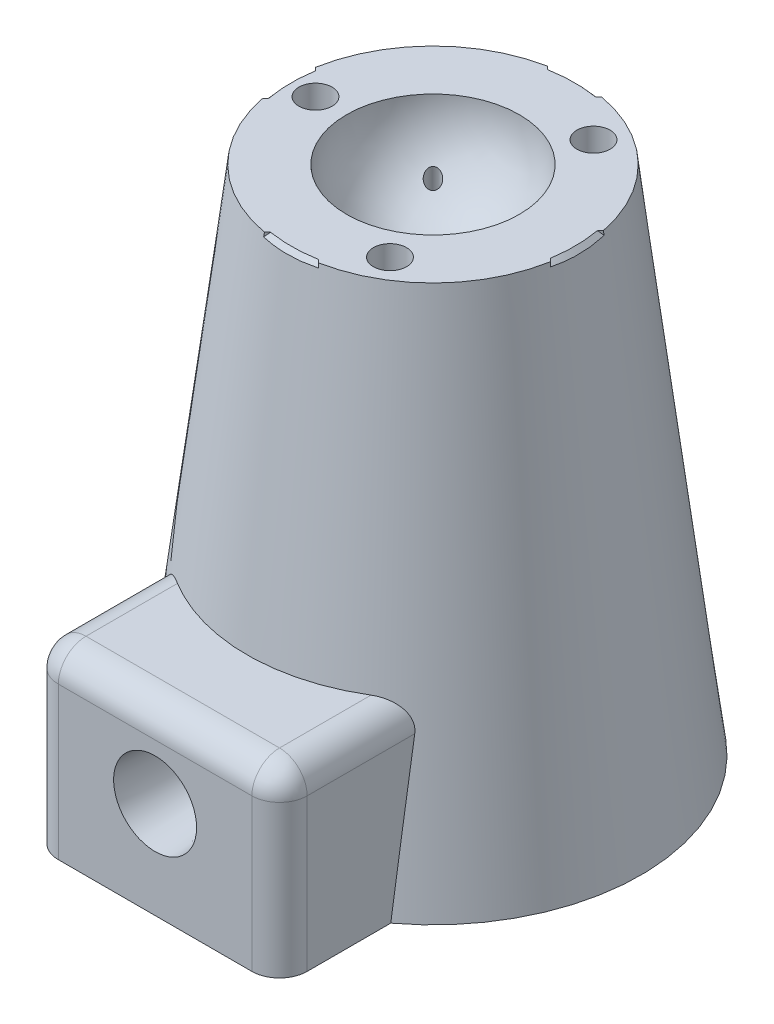
SolidWorks part; units mm, degrees
ref_plane "前视基准面" through (0, 0, 0) normal (0, 0, 1) x (1, 0, 0)
ref_plane "上视基准面" through (0, 0, 0) normal (0, 1, 0) x (1, 0, 0)
ref_plane "右视基准面" through (0, 0, 0) normal (1, 0, 0) x (0, 0, -1)
other "Configuration Table"
sketch "草图2" plane through (0, 0, 0) normal (0, 1, 0) x (1, 0, 0)
  line L1 (-28.1, 43.1) -> (28.1, 43.1)
  line L2 (-43.1, 28.1) -> (-43.1, -28.1)
  line L3 (-28.1, -43.1) -> (28.1, -43.1)
  line L4 (43.1, 28.1) -> (43.1, -28.1)
  line L5 (-43.1, 43.1) -> (43.1, -43.1) construction
  line L6 (-43.1, -43.1) -> (43.1, 43.1) construction
  arc A0 (-43.1, -28.1) -> (-28.1, -43.1) centre (-28.1, -28.1) ccw
  arc A1 (28.1, -43.1) -> (43.1, -28.1) centre (28.1, -28.1) ccw
  arc A2 (28.1, 43.1) -> (43.1, 28.1) centre (28.1, 28.1) cw
  arc A3 (-28.1, 43.1) -> (-43.1, 28.1) centre (-28.1, 28.1) ccw
  point P0 (0, 0)
  dimension "D3" = 15
  dimension "D1" = 86.2
  dimension "D2" = 86.2
extrude "凸台-拉伸1" add sketch "草图2" along normal blind 10
sketch "草图3" plane through (0, 10, 0) normal (0, 1, 0) x (1, 0, 0)
  line L0 (0, 6.25) -> (0, -6.25)
  arc A0 (0, 6.25) -> (0, -6.25) centre (0, 0) ccw
revolve "切除-旋转1" cut sketch "草图3" angle 360 about L0
ref_plane "基准面4" through (0, 0, 10) normal (0, 0, 1) x (1, 0, 0)
sketch "草图4" plane through (0, 10, 0) normal (0, 1, 0) x (1, 0, 0)
  line L0 (0, 0) -> (-37.5181, 37.5181) construction
sketch "草图5" plane through (0, 0, 0) normal (0, 0, 1) x (1, 0, 0)
  line L0 (0, 0) -> (0, 23.5244) construction
ref_plane "基准面2" through (0, 0, 0) normal (0.7071, 0, -0.7071) x (0, 1, 0)
sketch "草图22" plane through (0, 0, 0) normal (0, -1, 0) x (1, 0, 0)
  line L8 (-43.1, 28.1) -> (-43.1, -28.1)
  line L9 (-28.1, -43.1) -> (28.1, -43.1)
  line L10 (43.1, -28.1) -> (43.1, 28.1)
  line L11 (28.1, 43.1) -> (-28.1, 43.1)
  line L12 (-43.1, 28.1) -> (-43.1, -28.1)
  line L13 (-28.1, -43.1) -> (28.1, -43.1)
  line L14 (43.1, -28.1) -> (43.1, 28.1)
  line L15 (28.1, 43.1) -> (-28.1, 43.1)
  arc A8 (-28.1, 43.1) -> (-43.1, 28.1) centre (-28.1, 28.1) ccw
  arc A9 (-43.1, -28.1) -> (-28.1, -43.1) centre (-28.1, -28.1) ccw
  arc A10 (28.1, -43.1) -> (43.1, -28.1) centre (28.1, -28.1) ccw
  arc A11 (43.1, 28.1) -> (28.1, 43.1) centre (28.1, 28.1) ccw
  arc A12 (-28.1, 43.1) -> (-43.1, 28.1) centre (-28.1, 28.1) ccw
  arc A13 (-43.1, -28.1) -> (-28.1, -43.1) centre (-28.1, -28.1) ccw
  arc A14 (28.1, -43.1) -> (43.1, -28.1) centre (28.1, -28.1) ccw
  arc A15 (43.1, 28.1) -> (28.1, 43.1) centre (28.1, 28.1) ccw
  dimension "D1" = 0
extrude "凸台-拉伸2" add sketch "草图22" along normal blind 20
sketch "草图7" plane through (0, 0, 0) normal (0.7071, 0, -0.7071) x (0, 1, 0)
  line L0 (0.163, 0) -> (28.4458, 0) construction
  line L1 (0, 0) -> (23.5244, 0) construction
  line L2 (28.4458, 0) -> (-23.7376, 10.6911)
sweep "切除-扫描1" cut path "草图7" circular profile diameter 1 parameters "D3"=1
pattern_circular "阵列(圆周)1" count 4 over 360 about axis through (0, 10, 0) along (0, 1, 0) of "切除-扫描1"
ref_plane "基准面3" through (0, -20, 0) normal (0, 1, 0) x (1, 0, 0)
sketch "草图277" plane through (0, -20, 0) normal (0, 1, 0) x (1, 0, 0)
  line L1 (-28.1, -43.1) -> (28.1, -43.1)
  line L2 (-43.1, -28.1) -> (-43.1, 28.1)
  line L3 (-28.1, 43.1) -> (28.1, 43.1)
  line L4 (43.1, -28.1) -> (43.1, 28.1)
  line L5 (-43.1, -43.1) -> (43.1, 43.1) construction
  line L6 (-43.1, 43.1) -> (43.1, -43.1) construction
  arc A0 (-43.1, 28.1) -> (-28.1, 43.1) centre (-28.1, 28.1) cw
  arc A1 (28.1, 43.1) -> (43.1, 28.1) centre (28.1, 28.1) cw
  arc A2 (28.1, -43.1) -> (43.1, -28.1) centre (28.1, -28.1) ccw
  arc A3 (-28.1, -43.1) -> (-43.1, -28.1) centre (-28.1, -28.1) cw
  point P0 (0, 0)
  dimension "D3" = 15
  dimension "D1" = 86.2
  dimension "D2" = 86.2
extrude "凸台-拉伸5" add sketch "草图277" against normal blind 7
sketch "草图248" plane through (0, -20, 0) normal (0, 1, 0) x (1, 0, 0)
  line L0 (0, 0) -> (-7.0183, 7.0183)
  line L1 (0, 0) -> (-37.5181, 37.5181) construction
sweep "切除-扫描16" cut path "草图248" circular profile diameter 2.5 parameters "D3"=2.5
sketch "草图197" plane through (0, -20, 0) normal (0, 1, 0) x (1, 0, 0)
  line L0 (0, -3.5) -> (0, 3.5)
  arc A0 (0, 3.5) -> (0, -3.5) centre (0, 0) ccw
  dimension "D1" = 7
revolve "切除-旋转2" cut sketch "草图197" angle 360 about L0
sketch "草图303" plane through (0, -20, 0) normal (0, 1, 0) x (1, 0, 0)
  line L0 (0, 0) -> (-37.5181, 37.5181) construction
  line L1 (-7.0179, 5.7679) -> (-7.0179, 8.2679)
  arc A0 (-7.0179, 8.2679) -> (-7.0179, 5.7679) centre (-7.0179, 7.0179) ccw
  dimension "D1" = 2.5
revolve "切除-旋转5" cut sketch "草图303" angle 360 about L1
pattern_circular "阵列(圆周)3" count 4 over 360 about axis through (0, 0, 0) along (0, 1, 0) of "切除-扫描16", "切除-旋转5"
sketch "草图310" plane through (0, 10, 0) normal (0, 1, 0) x (1, 0, 0)
  line L0 (0, 0) -> (-37.5181, 37.5181) construction
  line L1 (28.1, 43.1) -> (-28.1, 43.1) construction
  circle A0 centre (-33.1, 33.1) radius 2.6
  circle A1 centre (33.1, 33.1) radius 2.6
  circle A2 centre (33.1, -33.1) radius 2.6
  circle A3 centre (-33.1, -33.1) radius 2.6
  point P15 (0, 0)
  dimension "D1" = 5.2
  dimension "D2" = 10
  dimension "D3" = 4
extrude "切除-拉伸2" cut sketch "草图310" against normal blind 10
sketch "草图311" plane through (0, 10, 0) normal (0, 1, 0) x (1, 0, 0)
  line L0 (-35.1, 26.6147) -> (-35.1, -26.6147)
  line L2 (-35.1, -26.6147) -> (-10.0896, -1.8063)
  line L3 (-35.1, 26.6147) -> (-10.119, 1.6337)
  line L4 (0, 0) -> (-37.5181, 37.5181) construction
  line L5 (-43.1, 28.1) -> (-43.1, -28.1) construction
  circle A3 centre (0, 0) radius 10.25
  arc A4 (-10.119, 1.6337) -> (-10.0896, -1.8063) centre (0, 0) ccw
  dimension "D2" = 6
  dimension "D4" = 8
  dimension "D1" = 4
sketch "草图316" plane through (0, -20, 0) normal (0, 1, 0) x (1, 0, 0)
  line L1 (-35.1, 26.6147) -> (-37.4121, 26.6147)
  line L2 (-35.1, 26.6147) -> (-35.1, -26.6147)
  line L3 (-35.1, -26.6147) -> (-37.4121, -26.6147)
  line L4 (-37.4121, 26.6147) -> (-37.4121, -26.6147)
loft "切除-放样5" cut profiles "草图311", "草图316"
sketch "草图317" plane through (0, -20, 0) normal (0, 1, 0) x (1, 0, 0)
  line L1 (-35.1, 26.6147) -> (-39.2405, 26.6147)
  line L2 (-35.1, 26.6147) -> (-35.1, -26.6147)
  line L3 (-35.1, -26.6147) -> (-39.2405, -26.6147)
  line L4 (-39.2405, 26.6147) -> (-39.2405, -26.6147)
extrude "凸台-拉伸6" add sketch "草图317" along normal blind 30
pattern_circular "阵列(圆周)5" count 4 over 360 about axis through (0, 10, 0) along (0, 1, 0) of "凸台-拉伸6", "切除-放样5"
sketch "草图326" plane through (0, -20, 0) normal (0, 1, 0) x (1, 0, 0)
  line L1 (-26.6147, -35.1) -> (26.6526, -35.1)
  line L2 (-26.6147, -35.1) -> (-26.6147, -32.173)
  line L3 (-26.6147, -32.173) -> (26.6526, -32.173)
  line L4 (26.6526, -35.1) -> (26.6526, -32.173)
extrude "凸台-拉伸7" add sketch "草图326" along normal blind 30
sketch "草图334" plane through (-43.1, 0, 0) normal (-1, 0, 0) x (0, 0, 1)
  line L0 (0, -27) -> (0, 1.7791) construction
  line L1 (-28.1, -27) -> (28.1, -27) construction
  line L2 (0, 0) -> (0, 23.5244) construction
  line L3 (-28.1, -8.5) -> (12.7158, -8.5) construction
  line L4 (-28.1, 10) -> (-28.1, -27) construction
  line L5 (-28.1, 10) -> (28.1, 10) construction
  line L6 (-17.1, 4) -> (17.1, 4)
  line L7 (-22.1, -1) -> (-22.1, -12)
  line L8 (-17.1, -17) -> (17.1, -17)
  line L9 (22.1, -1) -> (22.1, -12)
  line L10 (-22.1, 4) -> (22.1, -17) construction
  line L11 (-22.1, -17) -> (22.1, 4) construction
  arc A0 (17.1, -17) -> (22.1, -12) centre (17.1, -12) ccw
  arc A1 (17.1, 4) -> (22.1, -1) centre (17.1, -1) cw
  arc A2 (-22.1, -12) -> (-17.1, -17) centre (-17.1, -12) ccw
  arc A3 (-17.1, 4) -> (-22.1, -1) centre (-17.1, -1) ccw
  point P10 (0, -6.5)
  dimension "D2" = 5
  dimension "D1" = 10
  dimension "D3" = 6
  dimension "D4" = 6
extrude "切除-拉伸3" cut sketch "草图334" against normal blind 8
sketch "草图335" plane through (0, 0, -43.1) normal (0, 0, -1) x (-1, 0, 0)
  line L0 (-28.1, -27) -> (28.1, -27) construction
  line L1 (-17.1, 4) -> (17.1, 4)
  line L2 (-22.1, -1) -> (-22.1, -12)
  line L3 (-17.1, -17) -> (17.1, -17)
  line L4 (22.1, -1) -> (22.1, -12)
  line L5 (-22.1, 4) -> (22.1, -17) construction
  line L6 (-22.1, -17) -> (22.1, 4) construction
  line L7 (-28.1, 10) -> (28.1, 10) construction
  line L8 (-28.1, 10) -> (-28.1, -27) construction
  line L9 (28.1, 10) -> (28.1, -27) construction
  arc A0 (-22.1, -12) -> (-17.1, -17) centre (-17.1, -12) ccw
  arc A1 (17.1, -17) -> (22.1, -12) centre (17.1, -12) ccw
  arc A2 (17.1, 4) -> (22.1, -1) centre (17.1, -1) cw
  arc A3 (-17.1, 4) -> (-22.1, -1) centre (-17.1, -1) ccw
  point P0 (0, -6.5)
  dimension "D5" = 5
  dimension "D1" = 10
  dimension "D2" = 6
  dimension "D3" = 6
  dimension "D4" = 6
extrude "切除-拉伸4" cut sketch "草图335" against normal blind 8
sketch "草图336" plane through (43.1, 0, 0) normal (1, 0, 0) x (0, 0, -1)
  line L0 (0, 10) -> (37.5181, 10) construction
  line L1 (-17.1, 4) -> (17.1, 4)
  line L2 (-22.1, -1) -> (-22.1, -12)
  line L3 (-17.1, -17) -> (17.1, -17)
  line L4 (22.1, -1) -> (22.1, -12)
  line L5 (-22.1, 4) -> (22.1, -17) construction
  line L6 (-22.1, -17) -> (22.1, 4) construction
  line L7 (28.1, 10) -> (28.1, -27) construction
  line L8 (-28.1, 10) -> (-28.1, -27) construction
  line L9 (-28.1, -27) -> (28.1, -27) construction
  arc A0 (17.1, 4) -> (22.1, -1) centre (17.1, -1) cw
  arc A1 (17.1, -17) -> (22.1, -12) centre (17.1, -12) ccw
  arc A2 (-22.1, -12) -> (-17.1, -17) centre (-17.1, -12) ccw
  arc A3 (-17.1, 4) -> (-22.1, -1) centre (-17.1, -1) ccw
  point P0 (0, -6.5)
  dimension "D5" = 5
  dimension "D1" = 6
  dimension "D2" = 6
  dimension "D3" = 6
  dimension "D4" = 10
extrude "切除-拉伸5" cut sketch "草图336" against normal blind 8
sketch "草图164" plane through (0, 0, 43.1) normal (0, 0, 1) x (1, 0, 0)
  line L0 (47.41, -20) -> (-47.41, -20) construction
  circle A0 centre (0, -20) radius 4
extrude "切除-拉伸1" cut sketch "草图164" against normal blind 42 draft 4
sketch "草图337" plane through (0, 0, 43.1) normal (0, 0, 1) x (1, 0, 0)
  line L0 (0, 10) -> (-37.5181, 10) construction
  line L1 (-17.1, 4) -> (17.1, 4)
  line L2 (-22.1, -1) -> (-22.1, -8)
  line L3 (-17.1, -13) -> (17.1, -13)
  line L4 (22.1, -1) -> (22.1, -8)
  line L5 (-22.1, 4) -> (22.1, -13) construction
  line L6 (-22.1, -13) -> (22.1, 4) construction
  line L7 (-28.1, 10) -> (-28.1, -27) construction
  line L8 (28.1, 10) -> (28.1, -27) construction
  circle A0 centre (0, -20) radius 4 construction
  arc A1 (17.1, 4) -> (22.1, -1) centre (17.1, -1) cw
  arc A2 (17.1, -13) -> (22.1, -8) centre (17.1, -8) ccw
  arc A3 (-22.1, -8) -> (-17.1, -13) centre (-17.1, -8) ccw
  arc A4 (-17.1, 4) -> (-22.1, -1) centre (-17.1, -1) ccw
  point P0 (0, -4.5)
  dimension "D5" = 5
  dimension "D1" = 6
  dimension "D2" = 6
  dimension "D3" = 6
  dimension "D4" = 7
extrude "切除-拉伸6" cut sketch "草图337" against normal blind 11
sketch "草图338" plane through (0, 10, 0) normal (0, 1, 0) x (1, 0, 0)
  circle A0 centre (0, 0) radius 10.5
extrude "切除-拉伸7" cut sketch "草图338" against normal blind 40 draft 7 flip side to cut
ref_plane "基准面5" through (0, -27, 0) normal (0, 1, 0) x (1, 0, 0)
sketch "草图350" plane through (0, -27, 0) normal (0, 1, 0) x (1, 0, 0)
  line L0 (0, 0) -> (0, -24.1682) construction
  line L1 (-9, -12.0537) -> (-9, -20.1009)
  line L2 (-9, -20.1009) -> (9, -20.1009)
  line L3 (9, -20.1009) -> (9, -12.0537)
  circle A0 centre (0, 0) radius 15.043 construction
  circle A3 centre (0, 0) radius 15.043
  arc A4 (-9, -12.0537) -> (9, -12.0537) centre (0, 0) ccw
  dimension "D2" = 9
  dimension "D3" = 9
  dimension "D1" = 0
ref_plane "基准面6" through (0, -14, 0) normal (0, 1, 0) x (1, 0, 0)
sketch "草图351" plane through (0, -14, 0) normal (0, 1, 0) x (1, 0, 0)
  line L0 (-9, -20.1009) -> (-9, -8.7549)
  line L1 (-9, -20.1009) -> (9, -20.1009)
  line L2 (9, -20.1009) -> (9, -8.7549)
  arc A0 (-9, -8.7549) -> (9, -8.7549) centre (0, 0.2451) ccw
loft "放样1" add profiles "草图351", "草图350"
fillet "圆角2" radius 2 5 edges
sketch "草图353" plane through (0, 0, 20.1009) normal (0, 0, 1) x (1, 0, 0)
  circle A0 centre (0, -19.9924) radius 3
extrude "切除-拉伸8" cut sketch "草图353" against normal blind 20 draft 4.3
sketch "草图354" plane through (0, 10, 0) normal (0, 1, 0) x (1, 0, 0)
  circle A0 centre (-8.5, 0) radius 1.2
  circle A1 centre (0, 0) radius 6.25 construction
  circle A2 centre (4.25, 7.3612) radius 1.2
  circle A3 centre (4.25, -7.3612) radius 1.2
  point P10 (0, 0)
  dimension "D2" = 2.4
  dimension "D1" = 8.5
  dimension "D3" = 3
extrude "切除-拉伸9" cut sketch "草图354" against normal blind 6
sketch "草图355" plane through (0, -27, 0) normal (0, -1, 0) x (1, 0, 0)
  circle A0 centre (9.5064, 0) radius 2.4
  circle A1 centre (0.0064, -9.5) radius 2.4
  circle A2 centre (-9.4936, 0) radius 2.4
  circle A3 centre (0.0064, 9.5) radius 2.4
  point P11 (0.0064, 0)
  dimension "D1" = 4
  dimension "D3" = 4.8
  dimension "D2" = 9.5
extrude "切除-拉伸10" cut sketch "草图355" against normal blind 4
